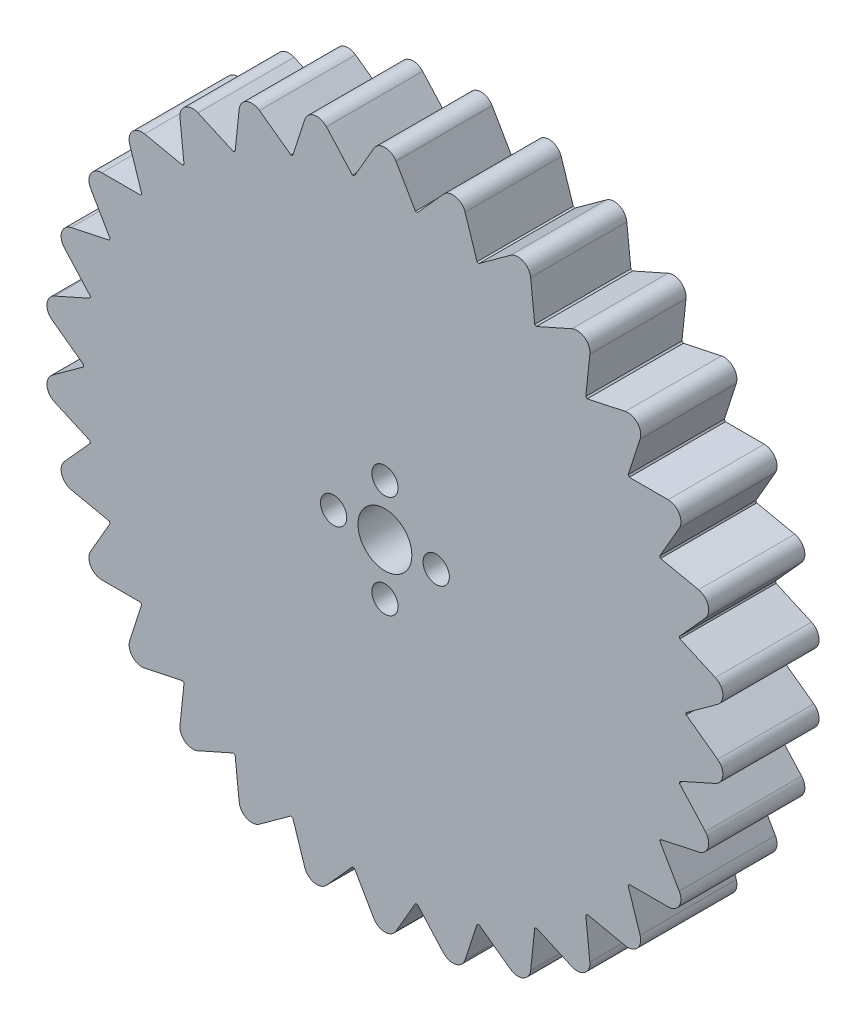
SolidWorks part; units mm, degrees
ref_plane "Front" through (0, 0, 0) normal (0, 0, 1) x (1, 0, 0)
ref_plane "Top" through (0, 0, 0) normal (0, 1, 0) x (1, 0, 0)
ref_plane "Right" through (0, 0, 0) normal (1, 0, 0) x (0, 0, -1)
sketch "Sketch1" plane through (0, 0, 0) normal (0, 0, 1) x (1, 0, 0)
  line L0 (0, 0) -> (0, 8) construction
  line L1 (0, 0) -> (0, 55) construction
  line L2 (-1.7321, 52) -> (-4.7582, 46.7585)
  line L3 (1.7321, 52) -> (4.7582, 46.7585)
  line L4 (12.5056, 50.5036) -> (14.3759, 44.7474)
  line L5 (9.1172, 51.2238) -> (5.0674, 46.726)
  line L6 (22.7326, 46.7999) -> (23.3653, 40.7807)
  line L7 (19.568, 48.2089) -> (14.6716, 44.6514)
  line L8 (31.9661, 41.0508) -> (31.3335, 35.0316)
  line L9 (29.1636, 43.087) -> (23.6345, 40.6253)
  line L10 (39.8025, 33.5076) -> (37.9322, 27.7515)
  line L11 (37.4846, 36.082) -> (31.5645, 34.8236)
  line L12 (45.8993, 24.5) -> (42.8732, 19.2585)
  line L13 (44.1673, 27.5) -> (38.115, 27.5)
  line L14 (49.9902, 14.4216) -> (45.9404, 9.9238)
  line L15 (48.9197, 17.7162) -> (42.9996, 18.9745)
  line L16 (51.8962, 3.7129) -> (46.9997, 0.1554)
  line L17 (51.5341, 7.158) -> (46.005, 9.6198)
  line L18 (51.5341, -7.158) -> (46.005, -9.6198)
  line L19 (51.8962, -3.7129) -> (46.9997, -0.1554)
  line L20 (48.9197, -17.7162) -> (42.9996, -18.9745)
  line L21 (49.9902, -14.4216) -> (45.9404, -9.9238)
  line L22 (44.1673, -27.5) -> (38.115, -27.5)
  line L23 (45.8993, -24.5) -> (42.8732, -19.2585)
  line L24 (37.4846, -36.082) -> (31.5645, -34.8236)
  line L25 (39.8025, -33.5076) -> (37.9322, -27.7515)
  line L26 (29.1636, -43.087) -> (23.6345, -40.6253)
  line L27 (31.9661, -41.0508) -> (31.3335, -35.0316)
  line L28 (19.568, -48.2089) -> (14.6716, -44.6514)
  line L29 (22.7326, -46.7999) -> (23.3653, -40.7807)
  line L30 (9.1172, -51.2238) -> (5.0674, -46.726)
  line L31 (12.5056, -50.5036) -> (14.3759, -44.7474)
  line L32 (-1.7321, -52) -> (-4.7582, -46.7585)
  line L33 (1.7321, -52) -> (4.7582, -46.7585)
  line L34 (-12.5056, -50.5036) -> (-14.3759, -44.7474)
  line L35 (-9.1172, -51.2238) -> (-5.0674, -46.726)
  line L36 (-22.7326, -46.7999) -> (-23.3653, -40.7807)
  line L37 (-19.568, -48.2089) -> (-14.6716, -44.6514)
  line L38 (-31.9661, -41.0508) -> (-31.3335, -35.0316)
  line L39 (-29.1636, -43.087) -> (-23.6345, -40.6253)
  line L40 (-39.8025, -33.5076) -> (-37.9322, -27.7515)
  line L41 (-37.4846, -36.082) -> (-31.5645, -34.8236)
  line L42 (-45.8993, -24.5) -> (-42.8732, -19.2585)
  line L43 (-44.1673, -27.5) -> (-38.115, -27.5)
  line L44 (-49.9902, -14.4216) -> (-45.9404, -9.9238)
  line L45 (-48.9197, -17.7162) -> (-42.9996, -18.9745)
  line L46 (-51.8962, -3.7129) -> (-46.9997, -0.1554)
  line L47 (-51.5341, -7.158) -> (-46.005, -9.6198)
  line L48 (-51.5341, 7.158) -> (-46.005, 9.6198)
  line L49 (-51.8962, 3.7129) -> (-46.9997, 0.1554)
  line L50 (-48.9197, 17.7162) -> (-42.9996, 18.9745)
  line L51 (-49.9902, 14.4216) -> (-45.9404, 9.9238)
  line L52 (-44.1673, 27.5) -> (-38.115, 27.5)
  line L53 (-45.8993, 24.5) -> (-42.8732, 19.2585)
  line L54 (-37.4846, 36.082) -> (-31.5645, 34.8236)
  line L55 (-39.8025, 33.5076) -> (-37.9322, 27.7515)
  line L56 (-29.1636, 43.087) -> (-23.6345, 40.6253)
  line L57 (-31.9661, 41.0508) -> (-31.3335, 35.0316)
  line L58 (-19.568, 48.2089) -> (-14.6716, 44.6514)
  line L59 (-22.7326, 46.7999) -> (-23.3653, 40.7807)
  line L60 (-9.1172, 51.2238) -> (-5.0674, 46.726)
  line L61 (-12.5056, 50.5036) -> (-14.3759, 44.7474)
  arc A0 (-4.7582, 46.7585) -> (-5.0674, 46.726) centre (0, 0) ccw
  circle A1 centre (0, 0) radius 55 construction
  circle A2 centre (0, 0) radius 4.2
  circle A3 centre (0, 8) radius 2.05
  circle A4 centre (8, 0) radius 2.05
  circle A5 centre (0, -8) radius 2.05
  circle A6 centre (-8, 0) radius 2.05
  arc A7 (-1.7321, 52) -> (1.7321, 52) centre (0, 51) cw
  arc A8 (9.1172, 51.2238) -> (12.5056, 50.5036) centre (10.6035, 49.8855) cw
  arc A9 (19.568, 48.2089) -> (22.7326, 46.7999) centre (20.7436, 46.5908) cw
  arc A10 (29.1636, 43.087) -> (31.9661, 41.0508) centre (29.977, 41.2599) cw
  arc A11 (37.4846, 36.082) -> (39.8025, 33.5076) centre (37.9004, 34.1257) cw
  arc A12 (44.1673, 27.5) -> (45.8993, 24.5) centre (44.1673, 25.5) cw
  arc A13 (48.9197, 17.7162) -> (49.9902, 14.4216) centre (48.5039, 15.7599) cw
  arc A14 (51.5341, 7.158) -> (51.8962, 3.7129) centre (50.7206, 5.331) cw
  arc A15 (51.8962, -3.7129) -> (51.5341, -7.158) centre (50.7206, -5.331) cw
  arc A16 (49.9902, -14.4216) -> (48.9197, -17.7162) centre (48.5039, -15.7599) cw
  arc A17 (45.8993, -24.5) -> (44.1673, -27.5) centre (44.1673, -25.5) cw
  arc A18 (39.8025, -33.5076) -> (37.4846, -36.082) centre (37.9004, -34.1257) cw
  arc A19 (31.9661, -41.0508) -> (29.1636, -43.087) centre (29.977, -41.2599) cw
  arc A20 (22.7326, -46.7999) -> (19.568, -48.2089) centre (20.7436, -46.5908) cw
  arc A21 (12.5056, -50.5036) -> (9.1172, -51.2238) centre (10.6035, -49.8855) cw
  arc A22 (1.7321, -52) -> (-1.7321, -52) centre (0, -51) cw
  arc A23 (-9.1172, -51.2238) -> (-12.5056, -50.5036) centre (-10.6035, -49.8855) cw
  arc A24 (-19.568, -48.2089) -> (-22.7326, -46.7999) centre (-20.7436, -46.5908) cw
  arc A25 (-29.1636, -43.087) -> (-31.9661, -41.0508) centre (-29.977, -41.2599) cw
  arc A26 (-37.4846, -36.082) -> (-39.8025, -33.5076) centre (-37.9004, -34.1257) cw
  arc A27 (-44.1673, -27.5) -> (-45.8993, -24.5) centre (-44.1673, -25.5) cw
  arc A28 (-48.9197, -17.7162) -> (-49.9902, -14.4216) centre (-48.5039, -15.7599) cw
  arc A29 (-51.5341, -7.158) -> (-51.8962, -3.7129) centre (-50.7206, -5.331) cw
  arc A30 (-51.8962, 3.7129) -> (-51.5341, 7.158) centre (-50.7206, 5.331) cw
  arc A31 (-49.9902, 14.4216) -> (-48.9197, 17.7162) centre (-48.5039, 15.7599) cw
  arc A32 (-45.8993, 24.5) -> (-44.1673, 27.5) centre (-44.1673, 25.5) cw
  arc A33 (-39.8025, 33.5076) -> (-37.4846, 36.082) centre (-37.9004, 34.1257) cw
  arc A34 (-31.9661, 41.0508) -> (-29.1636, 43.087) centre (-29.977, 41.2599) cw
  arc A35 (-22.7326, 46.7999) -> (-19.568, 48.2089) centre (-20.7436, 46.5908) cw
  arc A36 (-12.5056, 50.5036) -> (-9.1172, 51.2238) centre (-10.6035, 49.8855) cw
  arc A37 (-14.3759, 44.7474) -> (-14.6716, 44.6514) centre (0, 0) ccw
  arc A38 (-23.3653, 40.7807) -> (-23.6345, 40.6253) centre (0, 0) ccw
  arc A39 (-31.3335, 35.0316) -> (-31.5645, 34.8236) centre (0, 0) ccw
  arc A40 (-37.9322, 27.7515) -> (-38.115, 27.5) centre (0, 0) ccw
  arc A41 (-42.8732, 19.2585) -> (-42.9996, 18.9745) centre (0, 0) ccw
  arc A42 (-45.9404, 9.9238) -> (-46.005, 9.6198) centre (0, 0) ccw
  arc A43 (-46.9997, 0.1554) -> (-46.9997, -0.1554) centre (0, 0) ccw
  arc A44 (-46.005, -9.6198) -> (-45.9404, -9.9238) centre (0, 0) ccw
  arc A45 (-42.9996, -18.9745) -> (-42.8732, -19.2585) centre (0, 0) ccw
  arc A46 (-38.115, -27.5) -> (-37.9322, -27.7515) centre (0, 0) ccw
  arc A47 (-31.5645, -34.8236) -> (-31.3335, -35.0316) centre (0, 0) ccw
  arc A48 (-23.6345, -40.6253) -> (-23.3653, -40.7807) centre (0, 0) ccw
  arc A49 (-14.6716, -44.6514) -> (-14.3759, -44.7474) centre (0, 0) ccw
  arc A50 (-5.0674, -46.726) -> (-4.7582, -46.7585) centre (0, 0) ccw
  arc A51 (4.7582, -46.7585) -> (5.0674, -46.726) centre (0, 0) ccw
  arc A52 (14.3759, -44.7474) -> (14.6716, -44.6514) centre (0, 0) ccw
  arc A53 (23.3653, -40.7807) -> (23.6345, -40.6253) centre (0, 0) ccw
  arc A54 (31.3335, -35.0316) -> (31.5645, -34.8236) centre (0, 0) ccw
  arc A55 (37.9322, -27.7515) -> (38.115, -27.5) centre (0, 0) ccw
  arc A56 (42.8732, -19.2585) -> (42.9996, -18.9745) centre (0, 0) ccw
  arc A57 (45.9404, -9.9238) -> (46.005, -9.6198) centre (0, 0) ccw
  arc A58 (46.9997, -0.1554) -> (46.9997, 0.1554) centre (0, 0) ccw
  arc A59 (46.005, 9.6198) -> (45.9404, 9.9238) centre (0, 0) ccw
  arc A60 (42.9996, 18.9745) -> (42.8732, 19.2585) centre (0, 0) ccw
  arc A61 (38.115, 27.5) -> (37.9322, 27.7515) centre (0, 0) ccw
  arc A62 (31.5645, 34.8236) -> (31.3335, 35.0316) centre (0, 0) ccw
  arc A63 (23.6345, 40.6253) -> (23.3653, 40.7807) centre (0, 0) ccw
  arc A64 (14.6716, 44.6514) -> (14.3759, 44.7474) centre (0, 0) ccw
  arc A65 (5.0674, 46.726) -> (4.7582, 46.7585) centre (0, 0) ccw
  point P16 (0, 0)
  point P166 (0, 0)
  dimension "D1" = 110
  dimension "D2" = 94
  dimension "D3" = 8.4
  dimension "D5" = 4.1
  dimension "D9" = 2
  dimension "D4" = 8
  dimension "D7" = 30
  dimension "D8" = 30
  dimension "D6" = 4
  dimension "D10" = 30
extrude "Boss-Extrude1" add sketch "Sketch1" along normal blind 15
